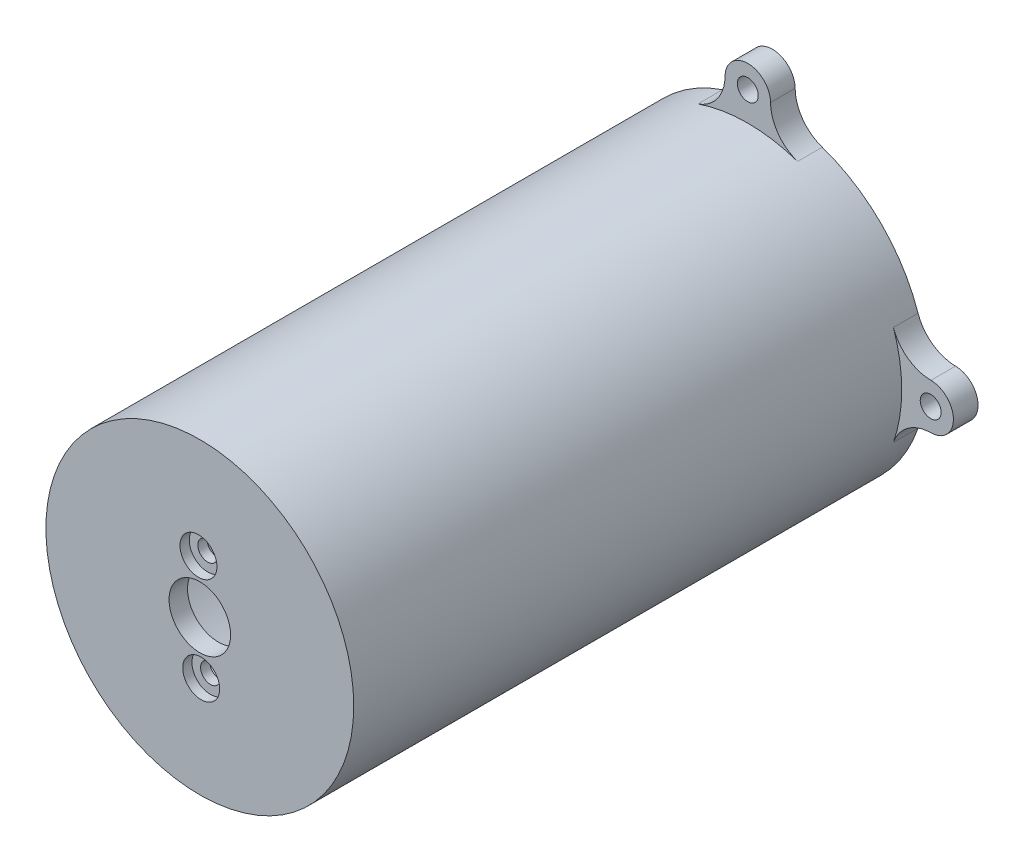
SolidWorks part; units mm, degrees
material "PLA"
ref_plane "Front Plane" through (0, 0, 0) normal (1, 0, 0) x (0, 1, 0)
ref_plane "Top Plane" through (0, 0, 0) normal (0, 0, 1) x (0, 1, 0)
ref_plane "Right Plane" through (0, 0, 0) normal (0, 1, 0) x (-1, 0, 0)
sketch "Sketch1" plane through (0, 0, 0) normal (0, 0, 1) x (0, 1, 0)
  circle A0 centre (0, 0) radius 24
  circle A1 centre (0, 0) radius 25
  dimension "D1" = 48
  dimension "D2" = 50
extrude "Boss-Extrude1" add sketch "Sketch1" along normal blind 90
sketch "Sketch2" plane through (90, 0, 90) normal (0, 0, 1) x (0, 1, 0)
  circle A0 centre (0, 90) radius 25
  circle A1 centre (0, 90) radius 5
  circle A4 centre (-8.4971, 89.7779) radius 1.6
  circle A5 centre (8.4971, 90.2221) radius 1.6
  dimension "D2" = 10
extrude "Boss-Extrude2" add sketch "Sketch2" along normal blind 3
sketch "Sketch3" plane through (0, 0, 93) normal (0, 0, 1) x (1, 0, 0)
  circle A0 centre (-0.2221, 8.4971) radius 3
  circle A1 centre (0.2221, -8.4971) radius 3
  dimension "D1" = 6
extrude "Cut-Extrude1" cut sketch "Sketch3" against normal blind 1.5
sketch "Sketch4" plane through (0, 0, 0) normal (0, 0, -1) x (1, 0, 0)
  line L0 (0, 41.6777) -> (0, -29.3467) construction
  circle A30 centre (0, 0) radius 25 construction
  arc A31 (-8.0884, 23.6554) -> (-23.6554, 8.0884) centre (0, 0) ccw
  circle A32 centre (0, 29.7067) radius 1.7
  arc A33 (3.6916, 29.7426) -> (-3.6916, 29.7426) centre (0, 29.7067) ccw
  arc A34 (3.6916, 29.7426) -> (8.0884, 23.6554) centre (10.1913, 29.8058) ccw
  arc A35 (-3.6916, 29.7426) -> (-8.0884, 23.6554) centre (-10.1913, 29.8058) cw
  circle A36 centre (29.7067, 0) radius 1.7
  arc A37 (29.7426, -3.6916) -> (29.7426, 3.6916) centre (29.7067, 0) ccw
  arc A38 (29.7426, -3.6916) -> (23.6554, -8.0884) centre (29.8058, -10.1913) ccw
  arc A39 (29.7426, 3.6916) -> (23.6554, 8.0884) centre (29.8058, 10.1913) cw
  circle A40 centre (0, -29.7067) radius 1.7
  arc A41 (-3.6916, -29.7426) -> (3.6916, -29.7426) centre (0, -29.7067) ccw
  arc A42 (-3.6916, -29.7426) -> (-8.0884, -23.6554) centre (-10.1913, -29.8058) ccw
  arc A43 (3.6916, -29.7426) -> (8.0884, -23.6554) centre (10.1913, -29.8058) cw
  circle A44 centre (-29.7067, 0) radius 1.7
  arc A45 (-29.7426, 3.6916) -> (-29.7426, -3.6916) centre (-29.7067, 0) ccw
  arc A46 (-29.7426, 3.6916) -> (-23.6554, 8.0884) centre (-29.8058, 10.1913) ccw
  arc A47 (-29.7426, -3.6916) -> (-23.6554, -8.0884) centre (-29.8058, -10.1913) cw
  arc A48 (-23.6554, -8.0884) -> (-8.0884, -23.6554) centre (0, 0) ccw
  arc A49 (8.0884, -23.6554) -> (23.6554, -8.0884) centre (0, 0) ccw
  arc A50 (23.6554, 8.0884) -> (8.0884, 23.6554) centre (0, 0) ccw
  circle A51 centre (0, 0) radius 24 construction
  circle A52 centre (0, 0) radius 24
  point P39 (0, 0)
  dimension "D1" = 4
extrude "Boss-Extrude3" add sketch "Sketch4" against normal blind 4
